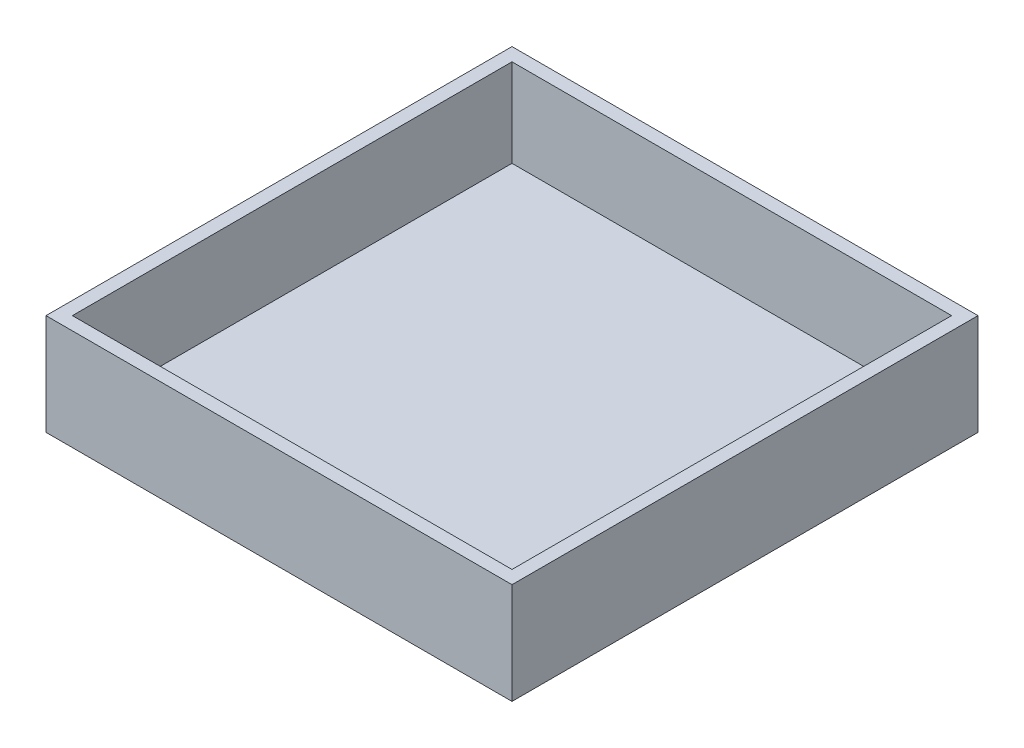
SolidWorks part; units mm, degrees
ref_plane "Front Plane" through (0, 0, 0) normal (0, 0, 1) x (1, 0, 0)
ref_plane "Top Plane" through (0, 0, 0) normal (0, 1, 0) x (1, 0, 0)
ref_plane "Right Plane" through (0, 0, 0) normal (1, 0, 0) x (0, 0, -1)
sketch "Sketch1" plane through (0, 0, 0) normal (0, 1, 0) x (1, 0, 0)
  line L1 (53, -53) -> (-53, -53)
  line L2 (53, -53) -> (53, 53)
  line L3 (53, 53) -> (-53, 53)
  line L4 (-53, -53) -> (-53, 53)
  line L5 (53, -53) -> (-53, 53) construction
  line L6 (53, 53) -> (-53, -53) construction
  point P0 (0, 0)
  dimension "D1" = 106
  dimension "D2" = 106
extrude "Boss-Extrude1" add sketch "Sketch1" along normal blind 23
shell "Shell1" thickness 3
